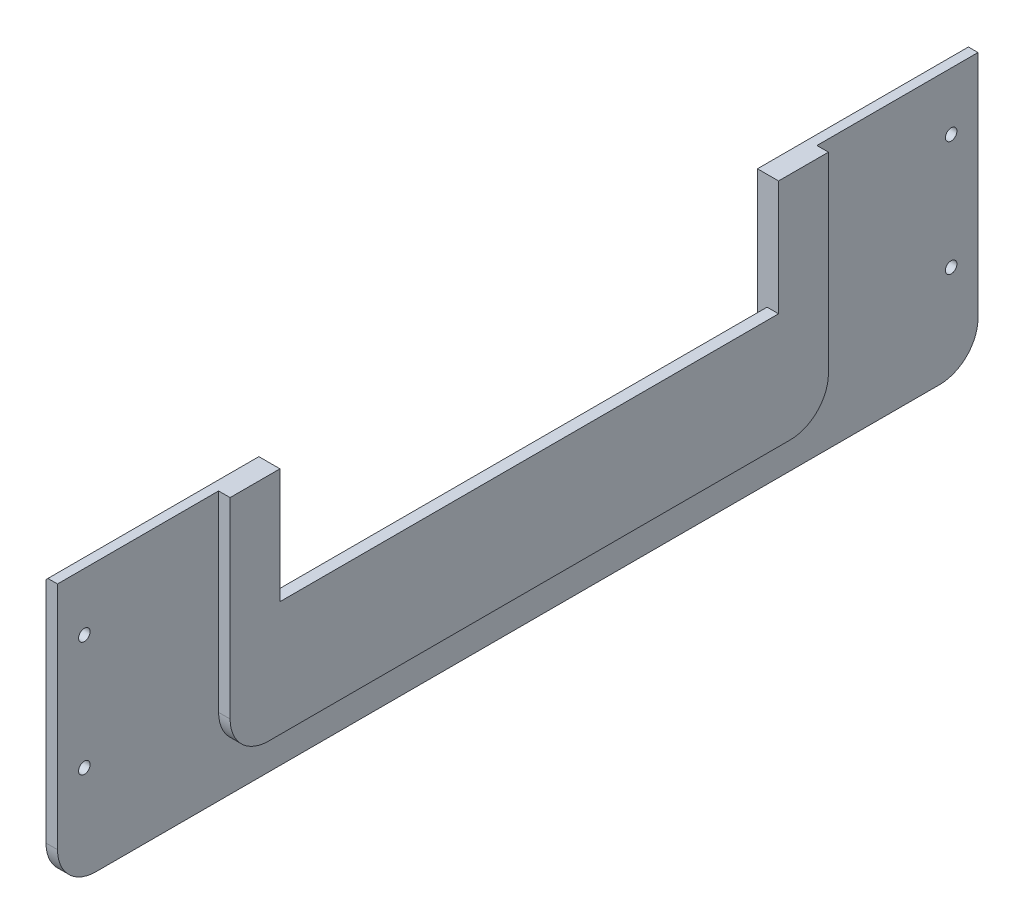
SolidWorks part; units mm, degrees
ref_plane "前视基准面" through (0, 0, 0) normal (0, 0, 1) x (1, 0, 0)
ref_plane "上视基准面" through (0, 0, 0) normal (0, 1, 0) x (1, 0, 0)
ref_plane "右视基准面" through (0, 0, 0) normal (1, 0, 0) x (0, 0, -1)
other "Configuration Table"
sketch "草图1" plane through (0, 0, 0) normal (1, 0, 0) x (0, 0, -1)
  line L1 (-120, 45) -> (120, 45)
  line L2 (-120, 45) -> (-120, -25)
  line L3 (-120, -25) -> (120, -25)
  line L4 (120, 45) -> (120, -25)
  dimension "D1" = 240
  dimension "D2" = 120
  dimension "D3" = 70
  dimension "D4" = 25
extrude "凸台-拉伸1" add sketch "草图1" along normal blind 3
sketch "草图4" plane through (3, 0, 0) normal (1, 0, 0) x (0, 0, -1)
  line L0 (120, 45) -> (-120, 45) construction
  line L1 (-78, 45) -> (78, 45)
  line L2 (-78, 45) -> (-78, -15)
  line L3 (-78, -15) -> (78, -15)
  line L4 (78, 45) -> (78, -15)
  dimension "D1" = 156
  dimension "D2" = 78
  dimension "D3" = 60
extrude "凸台-拉伸3" add sketch "草图4" along normal blind 3
sketch "草图5" plane through (0, 0, 0) normal (-1, 0, 0) x (0, 0, 1)
  line L0 (120, -25) -> (-120, -25) construction
  line L1 (0, 0) -> (0, -50000) construction
  circle A0 centre (113, 30) radius 1.5
  circle A1 centre (113, 0) radius 1.5
  circle A2 centre (-113, 0) radius 1.5
  circle A3 centre (-113, 30) radius 1.5
  dimension "D1" = 30
  dimension "D2" = 3
  dimension "D3" = 113
  dimension "D4" = 25
extrude "切除-拉伸1" cut sketch "草图5" against normal blind 20
fillet "圆角1" radius 10 2 edges at (1.5, -25, 120) (1.5, -25, -120)
fillet "圆角2" radius 10 2 edges at (4.5, -15, 78) (4.5, -15, -78)
sketch "草图7" plane through (0, 0, 0) normal (-1, 0, 0) x (0, 0, 1)
  line L0 (-65, 45) -> (-65, -5)
  line L1 (-120, 45) -> (120, 45) construction
  line L2 (-65, -5) -> (65, -5)
  line L3 (65, -5) -> (65, 45)
  line L4 (65, 45) -> (-65, 45)
  dimension "D1" = 130
  dimension "D2" = 65
  dimension "D3" = 5
extrude "切除-拉伸2" cut sketch "草图7" against normal blind 3
sketch "草图8" plane through (3, 0, 0) normal (-1, 0, 0) x (0, 0, 1)
  line L0 (65, -5) -> (65, 45) construction
  line L1 (-65, 45) -> (65, 45)
  line L2 (-65, 45) -> (-65, 15)
  line L3 (-65, 15) -> (65, 15)
  line L4 (65, 45) -> (65, 15)
  dimension "D1" = 30
extrude "切除-拉伸3" cut sketch "草图8" against normal blind 3
chamfer "倒角1" distance 0.5 angle 45 1 edges at (0, 45, 92.5)
chamfer "倒角2" distance 0.5 angle 45 3 edges at (0, 19.75, 65) (0, -5, 0) (0, 19.75, -65)
